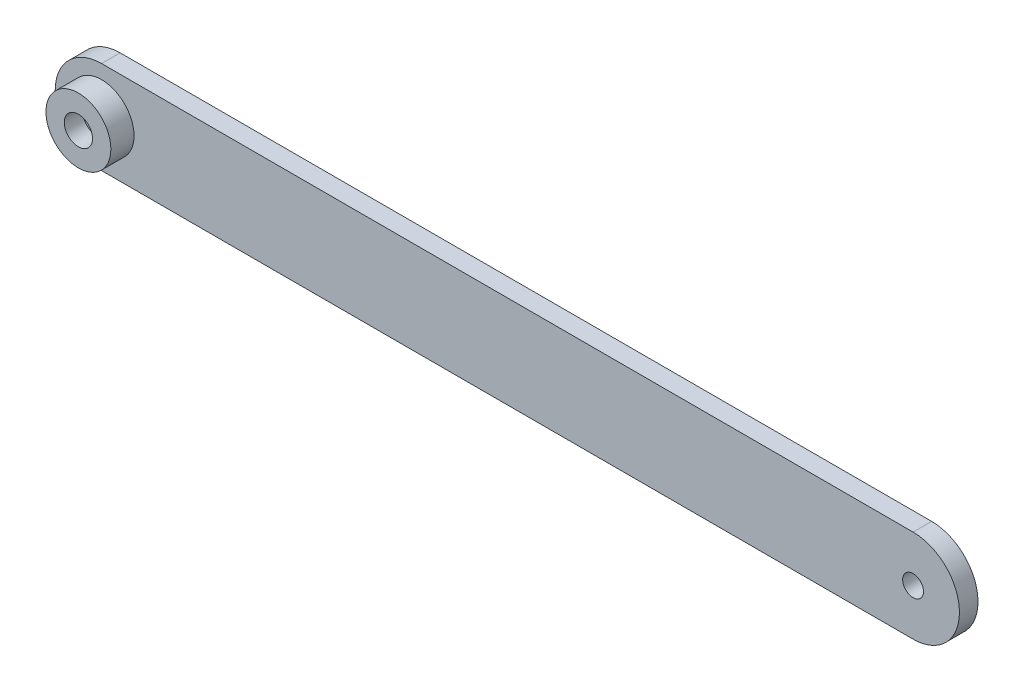
SolidWorks part; units mm, degrees
material "PET"
ref_plane "Front Plane" through (0, 0, 0) normal (0, 0, 1) x (1, 0, 0)
ref_plane "Top Plane" through (0, 0, 0) normal (0, 1, 0) x (1, 0, 0)
ref_plane "Right Plane" through (0, 0, 0) normal (1, 0, 0) x (0, 0, -1)
sketch "Sketch1" plane through (0, 0, 0) normal (0, 0, 1) x (1, 0, 0)
  line L0 (0, 0) -> (175, 0) construction
  line L1 (0, 10) -> (175, 10)
  line L2 (0, -10) -> (175, -10)
  arc A0 (0, 10) -> (0, -10) centre (0, 0) ccw
  arc A1 (175, -10) -> (175, 10) centre (175, 0) ccw
  circle A3 centre (175, 0) radius 2.25
  circle A9 centre (0, 0) radius 1
  point P3 (87.5, 0)
  dimension "D1" = 10
  dimension "D3" = 4.5
  dimension "D4" = 2
  dimension "D2" = 175
extrude "Boss-Extrude1" add sketch "Sketch1" along normal mid plane 4
sketch "Sketch4" plane through (0, 0, 2) normal (0, 0, 1) x (1, 0, 0)
  circle A0 centre (0, 0) radius 7
  circle A1 centre (0, 0) radius 1 construction
  circle A2 centre (0, 0) radius 1
  dimension "D1" = 14
extrude "Boss-Extrude2" add sketch "Sketch4" along normal blind 1
sketch "Sketch5" plane through (0, 0, 3) normal (0, 0, 1) x (1, 0, 0)
  circle A0 centre (0, 0) radius 7 construction
  circle A1 centre (0, 0) radius 7
  circle A2 centre (0, 0) radius 3.05
  dimension "D1" = 6.1
extrude "Boss-Extrude3" add sketch "Sketch5" along normal blind 4
sketch "Sketch6" plane through (0, 0, -2) normal (0, 0, -1) x (-1, 0, 0)
  line L0 (0, 2.0758) -> (0, 2.375) construction
  line L1 (-0.3247, 2.0503) -> (0, 2.375)
  line L2 (0.3247, 2.0503) -> (0, 2.375)
  line L3 (0.3247, 2.0503) -> (0.7339, 2.2588)
  line L4 (0.9424, 1.8496) -> (0.7339, 2.2588)
  line L5 (0.9424, 1.8496) -> (1.396, 1.9214)
  line L6 (1.4678, 1.4678) -> (1.396, 1.9214)
  line L7 (1.4678, 1.4678) -> (1.9214, 1.396)
  line L8 (1.8496, 0.9424) -> (1.9214, 1.396)
  line L9 (1.8496, 0.9424) -> (2.2588, 0.7339)
  line L10 (2.0503, 0.3247) -> (2.2588, 0.7339)
  line L11 (2.0503, 0.3247) -> (2.375, 0)
  line L12 (2.0503, -0.3247) -> (2.375, 0)
  line L13 (2.0503, -0.3247) -> (2.2587, -0.7339)
  line L14 (1.8496, -0.9424) -> (2.2587, -0.7339)
  line L15 (1.8496, -0.9424) -> (1.9214, -1.396)
  line L16 (1.4678, -1.4678) -> (1.9214, -1.396)
  line L17 (1.4678, -1.4678) -> (1.396, -1.9214)
  line L18 (0.9424, -1.8496) -> (1.396, -1.9214)
  line L19 (0.9424, -1.8496) -> (0.7339, -2.2588)
  line L20 (0.3247, -2.0503) -> (0.7339, -2.2588)
  line L21 (0.3247, -2.0503) -> (0, -2.375)
  line L22 (-0.3247, -2.0503) -> (0, -2.375)
  line L23 (-0.3247, -2.0503) -> (-0.7339, -2.2588)
  line L24 (-0.9424, -1.8496) -> (-0.7339, -2.2588)
  line L25 (-0.9424, -1.8496) -> (-1.396, -1.9214)
  line L26 (-1.4678, -1.4678) -> (-1.396, -1.9214)
  line L27 (-1.4678, -1.4678) -> (-1.9214, -1.396)
  line L28 (-1.8496, -0.9424) -> (-1.9214, -1.396)
  line L29 (-1.8496, -0.9424) -> (-2.2588, -0.7339)
  line L30 (-2.0503, -0.3247) -> (-2.2588, -0.7339)
  line L31 (-2.0503, -0.3247) -> (-2.375, 0)
  line L32 (-2.0503, 0.3247) -> (-2.375, 0)
  line L33 (-2.0503, 0.3247) -> (-2.2588, 0.7339)
  line L34 (-1.8496, 0.9424) -> (-2.2588, 0.7339)
  line L35 (-1.8496, 0.9424) -> (-1.9214, 1.396)
  line L36 (-1.4678, 1.4678) -> (-1.9214, 1.396)
  line L37 (-1.4678, 1.4678) -> (-1.396, 1.9214)
  line L38 (-0.9424, 1.8496) -> (-1.396, 1.9214)
  line L39 (-0.9424, 1.8496) -> (-0.7339, 2.2588)
  line L40 (-0.3247, 2.0503) -> (-0.7339, 2.2588)
  circle A0 centre (0, 0) radius 2.375 construction
  circle A1 centre (0, 0) radius 2.0758 construction
  circle A3 centre (0, 0) radius 1 construction
  point P67 (0, 0)
  dimension "D1" = 20
  dimension "D2" = 4.75
  dimension "D3" = 45
extrude "Cut-Extrude1" cut sketch "Sketch6" against normal blind 3
